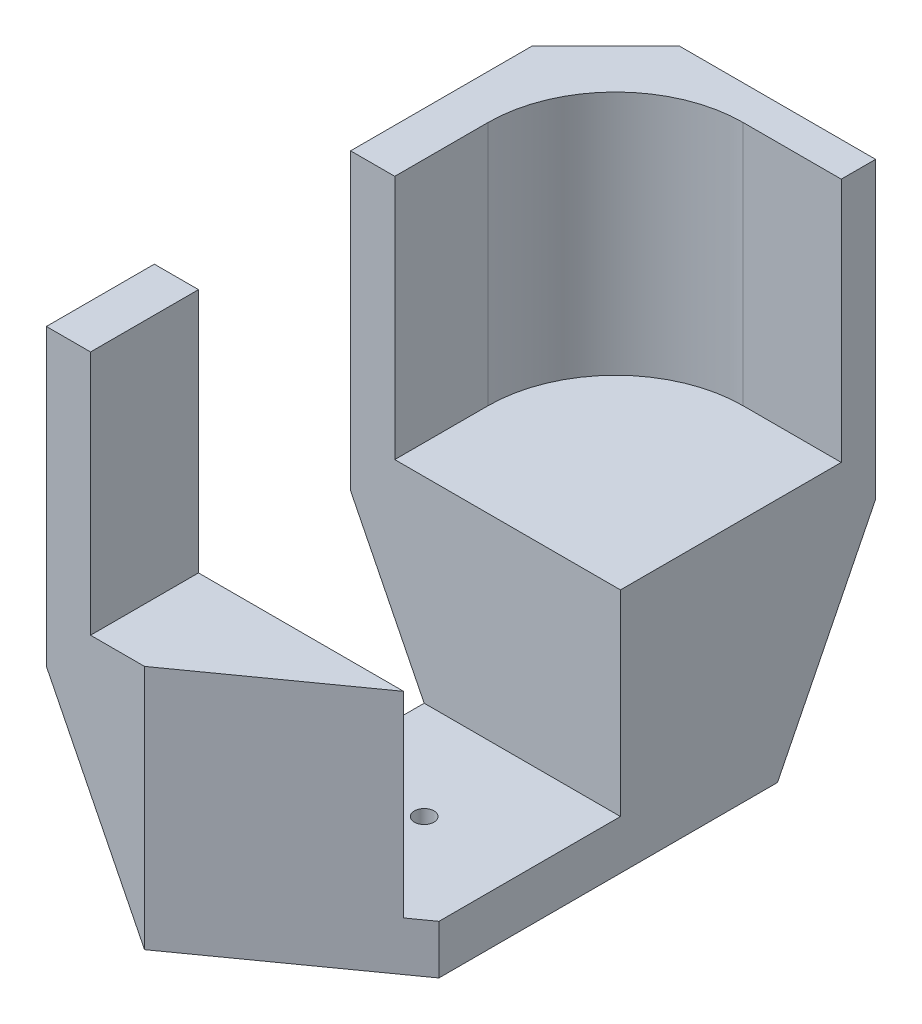
SolidWorks part; units mm, degrees
ref_plane "前视基准面" through (0, 0, 0) normal (0, 0, 1) x (1, 0, 0)
ref_plane "上视基准面" through (0, 0, 0) normal (0, 1, 0) x (1, 0, 0)
ref_plane "右视基准面" through (0, 0, 0) normal (1, 0, 0) x (0, 0, -1)
sketch "草图1" plane through (0, 0, 0) normal (0, 1, 0) x (1, 0, 0)
  line L0 (-35, 72) -> (-35, -42)
  line L1 (-35, -42) -> (-15, -42)
  line L2 (-15, -42) -> (20, -17)
  line L3 (20, -17) -> (20, 14.0256)
  line L4 (20, 14.0256) -> (20, 72)
  line L5 (20, 72) -> (-35, 72)
  circle A0 centre (0, 0) radius 2
  dimension "D1" = 4
  dimension "D2" = 114
  dimension "D3" = 25
  dimension "D4" = 20
  dimension "D5" = 35
  dimension "D7" = 72
  dimension "D8" = 20
extrude "凸台-拉伸1" add sketch "草图1" along normal blind 50
chamfer "倒角1" distance 15 angle 45 1 edges at (-35, 25, -72)
sketch "草图2" plane through (0, 50, 0) normal (0, 1, 0) x (1, 0, 0)
  line L0 (-35, 57) -> (-35, -42) construction
  line L1 (20, 72) -> (-20, 72) construction
  line L2 (-26, 39) -> (-26, -42)
  line L3 (-35, -42) -> (-15, -42) construction
  line L4 (-26, -42) -> (-35, -42)
  line L5 (-35, -42) -> (-35, 57)
  line L6 (-35, 57) -> (-20, 72)
  line L7 (-20, 72) -> (20, 72)
  line L8 (20, 72) -> (20, 65)
  line L9 (20, -17) -> (20, 72) construction
  line L10 (20, 65) -> (0, 65)
  arc A0 (0, 65) -> (-26, 39) centre (0, 39) ccw
  dimension "D3" = 52
  dimension "D1" = 35
  dimension "D2" = 33
extrude "凸台-拉伸2" add sketch "草图2" along normal blind 50
sketch "草图3" plane through (0, 50, 0) normal (0, 1, 0) x (1, 0, 0)
  line L0 (-35, 57) -> (-35, -42) construction
  line L1 (-35, 20) -> (20, 20)
  line L2 (-35, 20) -> (-35, -20)
  line L3 (-35, -20) -> (20, -20)
  line L4 (20, 20) -> (20, -20)
  dimension "D1" = 40
  dimension "D2" = 20
extrude "切除-拉伸1" cut sketch "草图3" against normal blind 40 and the other way blind 50
sketch "草图4" plane through (0, 0, -72) normal (0, 0, -1) x (-1, 0, 0)
  line L0 (15, 0) -> (35, 40)
  line L1 (-20, 0) -> (20, 0) construction
  line L2 (35, 100) -> (35, 0) construction
  line L3 (35, 40) -> (35, 0)
  line L4 (35, 0) -> (15, 0)
  dimension "D1" = 20
  dimension "D2" = 40
extrude "切除-拉伸2" cut sketch "草图4" against normal through all
sketch "草图5" plane through (20, 0, 0) normal (1, 0, 0) x (0, 0, -1)
  line L0 (52, 0) -> (72, 0)
  line L1 (-17, 0) -> (72, 0) construction
  line L2 (72, 0) -> (72, 40)
  line L3 (72, 100) -> (72, 0) construction
  line L4 (72, 40) -> (52, 0)
  dimension "D1" = 20
  dimension "D2" = 40
extrude "切除-拉伸3" cut sketch "草图5" against normal through all
chamfer "倒角2" distance 13.693 1 edges at (-21.25, 12.5, -58.25)
